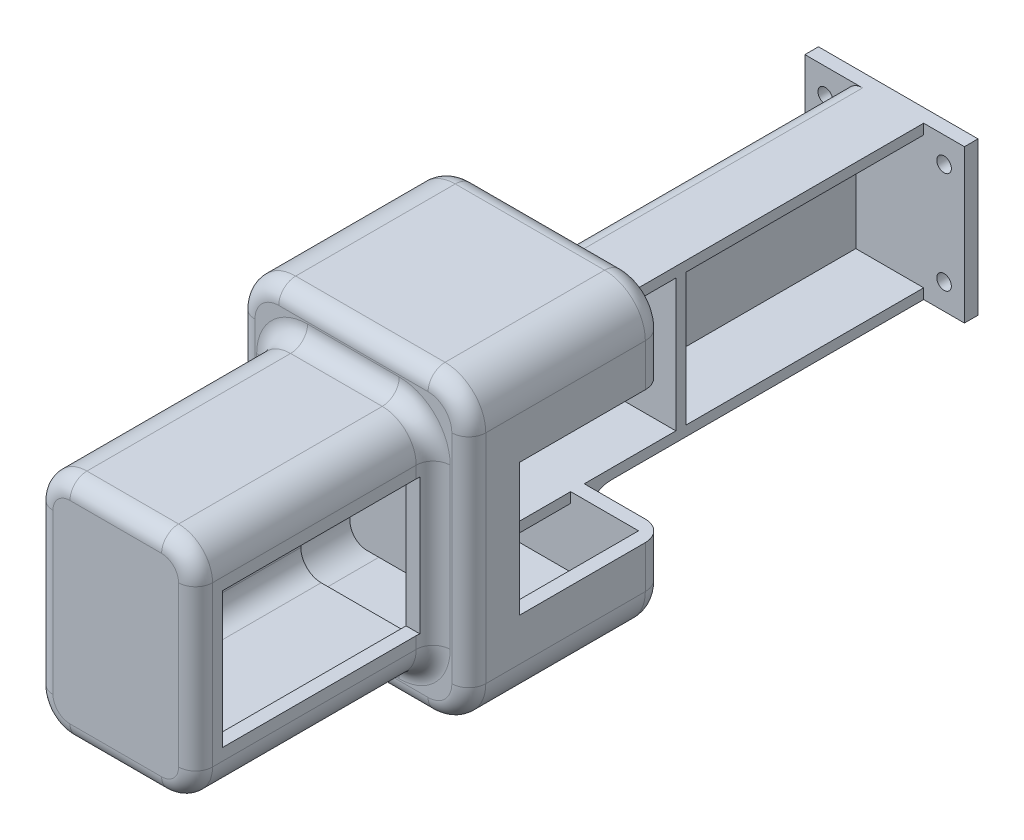
SolidWorks part; units mm, degrees
ref_plane "Front Plane" through (0, 0, 0) normal (0, 0, 1) x (1, 0, 0)
ref_plane "Top Plane" through (0, 0, 0) normal (0, 1, 0) x (1, 0, 0)
ref_plane "Right Plane" through (0, 0, 0) normal (1, 0, 0) x (0, 0, -1)
sketch "草圖1" plane through (0, 0, 0) normal (0, 0, 1) x (1, 0, 0)
  line L0 (-13, -22.5) -> (10, -22.5)
  line L1 (10, -22.5) -> (10, -19.5)
  line L2 (10, -19.5) -> (-10, -19.5)
  line L3 (-10, -19.5) -> (-10, 19.5)
  line L4 (-10, 19.5) -> (10, 19.5)
  line L5 (10, 19.5) -> (10, 22.5)
  line L6 (10, 22.5) -> (-13, 22.5)
  line L7 (-13, 22.5) -> (-13, -22.5)
extrude "填料-伸長1" add sketch "草圖1" along normal blind 150
fillet "圓角1" radius 5 2 edges at (-13, 22.5, 75) (-13, -22.5, 75)
sketch "草圖2" plane through (0, 0, 0) normal (0, 0, 1) x (1, 0, 0)
  line L0 (-25, -22.5) -> (22, -22.5)
  line L1 (22, -22.5) -> (22, 22.5)
  line L2 (22, 22.5) -> (-25, 22.5)
  line L3 (-25, 22.5) -> (-25, -22.5)
  circle A0 centre (-19, 15) radius 2.15
  circle A1 centre (-19, -15) radius 2.15
  circle A2 centre (16, 15) radius 2.15
  circle A3 centre (16, -15) radius 2.15
extrude "填料-伸長2" add sketch "草圖2" along normal blind 4
sketch "草圖3" plane through (0, 0, 0) normal (0, 0, 1) x (1, 0, 0)
  line L0 (-10.5, -20) -> (10, -20)
  line L1 (10, -20) -> (10, 20)
  line L2 (10, 20) -> (-10.5, 20)
  line L3 (-10.5, 20) -> (-10.5, -20)
extrude "填料-伸長3" add sketch "草圖3" along normal blind 3 from offset 74
sketch "草圖4" plane through (0, 0, 0) normal (0, 0, 1) x (1, 0, 0)
  line L0 (-10.5, -20) -> (10, -20)
  line L1 (10, -20) -> (10, 20)
  line L2 (10, 20) -> (-10.5, 20)
  line L3 (-10.5, 20) -> (-10.5, -20)
extrude "填料-伸長4" add sketch "草圖4" along normal blind 3 from offset 147
sketch "草圖5" plane through (0, 0, 0) normal (0, 0, 1) x (1, 0, 0)
  line L0 (34, -32) -> (34, 32)
  line L1 (22, 44) -> (-22, 44)
  line L2 (-34, 32) -> (-34, -32)
  line L3 (-22, -44) -> (22, -44)
  arc A0 (22, -44) -> (34, -32) centre (22, -32) ccw
  arc A1 (34, 32) -> (22, 44) centre (22, 32) ccw
  arc A2 (-22, 44) -> (-34, 32) centre (-22, 32) ccw
  arc A3 (-34, -32) -> (-22, -44) centre (-22, -32) ccw
extrude "填料-伸長5" add sketch "草圖5" along normal blind 4 from offset 104
sketch "草圖6" plane through (0, 0, 0) normal (0, 0, 1) x (1, 0, 0)
  line L0 (34, -32) -> (34, 32)
  line L1 (22, 44) -> (-22, 44)
  line L2 (-34, 32) -> (-34, -32)
  line L3 (-22, -44) -> (22, -44)
  line L4 (30, -32) -> (30, 32)
  line L5 (22, 40) -> (-22, 40)
  line L6 (-30, 32) -> (-30, -32)
  line L7 (-22, -40) -> (22, -40)
  arc A0 (22, -44) -> (34, -32) centre (22, -32) ccw
  arc A1 (34, 32) -> (22, 44) centre (22, 32) ccw
  arc A2 (-22, 44) -> (-34, 32) centre (-22, 32) ccw
  arc A3 (-34, -32) -> (-22, -44) centre (-22, -32) ccw
  arc A4 (22, -40) -> (30, -32) centre (22, -32) ccw
  arc A5 (30, 32) -> (22, 40) centre (22, 32) ccw
  arc A6 (-22, 40) -> (-30, 32) centre (-22, 32) ccw
  arc A7 (-30, -32) -> (-22, -40) centre (-22, -32) ccw
extrude "填料-伸長6" add sketch "草圖6" along normal blind 50 from offset 108
sketch "草圖7" plane through (0, 0, 0) normal (0, 0, 1) x (1, 0, 0)
  line L0 (34, -32) -> (34, 32)
  line L1 (22, 44) -> (-22, 44)
  line L2 (-34, 32) -> (-34, -32)
  line L3 (-22, -44) -> (22, -44)
  arc A0 (22, -44) -> (34, -32) centre (22, -32) ccw
  arc A1 (34, 32) -> (22, 44) centre (22, 32) ccw
  arc A2 (-22, 44) -> (-34, 32) centre (-22, 32) ccw
  arc A3 (-34, -32) -> (-22, -44) centre (-22, -32) ccw
extrude "填料-伸長7" add sketch "草圖7" along normal blind 4 from offset 158
sketch "草圖8" plane through (0, 0, 0) normal (0, 0, 1) x (1, 0, 0)
  line L0 (23.5, -23.5) -> (23.5, 23.5)
  line L1 (13.5, 33.5) -> (-13.5, 33.5)
  line L2 (-23.5, 23.5) -> (-23.5, -23.5)
  line L3 (-13.5, -33.5) -> (13.5, -33.5)
  line L4 (19.5, -23.5) -> (19.5, 23.5)
  line L5 (13.5, 29.5) -> (-13.5, 29.5)
  line L6 (-19.5, 23.5) -> (-19.5, -23.5)
  line L7 (-13.5, -29.5) -> (13.5, -29.5)
  arc A0 (13.5, -33.5) -> (23.5, -23.5) centre (13.5, -23.5) ccw
  arc A1 (23.5, 23.5) -> (13.5, 33.5) centre (13.5, 23.5) ccw
  arc A2 (-13.5, 33.5) -> (-23.5, 23.5) centre (-13.5, 23.5) ccw
  arc A3 (-23.5, -23.5) -> (-13.5, -33.5) centre (-13.5, -23.5) ccw
  arc A4 (13.5, -29.5) -> (19.5, -23.5) centre (13.5, -23.5) ccw
  arc A5 (19.5, 23.5) -> (13.5, 29.5) centre (13.5, 23.5) ccw
  arc A6 (-13.5, 29.5) -> (-19.5, 23.5) centre (-13.5, 23.5) ccw
  arc A7 (-19.5, -23.5) -> (-13.5, -29.5) centre (-13.5, -23.5) ccw
extrude "填料-伸長8" add sketch "草圖8" along normal blind 66 from offset 162
sketch "草圖9" plane through (0, 0, 0) normal (0, 0, 1) x (1, 0, 0)
  line L0 (23.5, -23.5) -> (23.5, 23.5)
  line L1 (13.5, 33.5) -> (-13.5, 33.5)
  line L2 (-23.5, 23.5) -> (-23.5, -23.5)
  line L3 (-13.5, -33.5) -> (13.5, -33.5)
  arc A0 (13.5, -33.5) -> (23.5, -23.5) centre (13.5, -23.5) ccw
  arc A1 (23.5, 23.5) -> (13.5, 33.5) centre (13.5, 23.5) ccw
  arc A2 (-13.5, 33.5) -> (-23.5, 23.5) centre (-13.5, 23.5) ccw
  arc A3 (-23.5, -23.5) -> (-13.5, -33.5) centre (-13.5, -23.5) ccw
extrude "填料-伸長9" add sketch "草圖9" along normal blind 4 from offset 228
fillet "圓角2" radius 8 5 edges at (-11.5355, -21.0355, 104) (1, 22.5, 104) (-13, 0, 104) (1, -22.5, 104) (-11.5355, 21.0355, 104)
fillet "圓角3" radius 6 8 edges at (30.4853, -40.4853, 104) (34, 0, 104) (30.4853, 40.4853, 104) (0, 44, 104) (-30.4853, 40.4853, 104) (-34, 0, 104) (-30.4853, -40.4853, 104) (0, -44, 104)
fillet "圓角4" radius 5 8 edges at (30.4853, -40.4853, 162) (34, 0, 162) (30.4853, 40.4853, 162) (0, 44, 162) (-30.4853, 40.4853, 162) (-34, 0, 162) (-30.4853, -40.4853, 162) (0, -44, 162)
fillet "圓角5" radius 5 8 edges at (20.5711, -30.5711, 162) (23.5, 0, 162) (20.5711, 30.5711, 162) (0, 33.5, 162) (-20.5711, 30.5711, 162) (-23.5, 0, 162) (-20.5711, -30.5711, 162) (0, -33.5, 162)
fillet "圓角6" radius 5 8 edges at (20.5711, -30.5711, 232) (23.5, 0, 232) (20.5711, 30.5711, 232) (0, 33.5, 232) (-20.5711, 30.5711, 232) (-23.5, 0, 232) (-20.5711, -30.5711, 232) (0, -33.5, 232)
sketch "草圖10" plane through (0, 0, 0) normal (0, 0, 1) x (1, 0, 0)
  line L0 (-10, -19.5) -> (39, -19.5)
  line L1 (39, -19.5) -> (39, 19.5)
  line L2 (39, 19.5) -> (-10, 19.5)
  line L3 (-10, 19.5) -> (-10, -19.5)
extrude "除料-伸長1" cut sketch "草圖10" along normal blind 70 from offset 77
sketch "草圖11" plane through (0, 0, 0) normal (0, 0, 1) x (1, 0, 0)
  line L0 (19.5, -23.5) -> (19.5, 23.5)
  line L1 (13.5, 29.5) -> (-13.5, 29.5)
  line L2 (-19.5, 23.5) -> (-19.5, -23.5)
  line L3 (-13.5, -29.5) -> (13.5, -29.5)
  arc A0 (13.5, -29.5) -> (19.5, -23.5) centre (13.5, -23.5) ccw
  arc A1 (19.5, 23.5) -> (13.5, 29.5) centre (13.5, 23.5) ccw
  arc A2 (-13.5, 29.5) -> (-19.5, 23.5) centre (-13.5, 23.5) ccw
  arc A3 (-19.5, -23.5) -> (-13.5, -29.5) centre (-13.5, -23.5) ccw
extrude "除料-伸長2" cut sketch "草圖11" along normal blind 8 from offset 157
sketch "草圖12" plane through (0, 0, 0) normal (0, 0, 1) x (1, 0, 0)
  line L0 (17.5, -20) -> (28.5, -20)
  line L1 (28.5, -20) -> (28.5, 20)
  line L2 (28.5, 20) -> (17.5, 20)
  line L3 (17.5, 20) -> (17.5, -20)
extrude "除料-伸長3" cut sketch "草圖12" along normal blind 58 from offset 166
